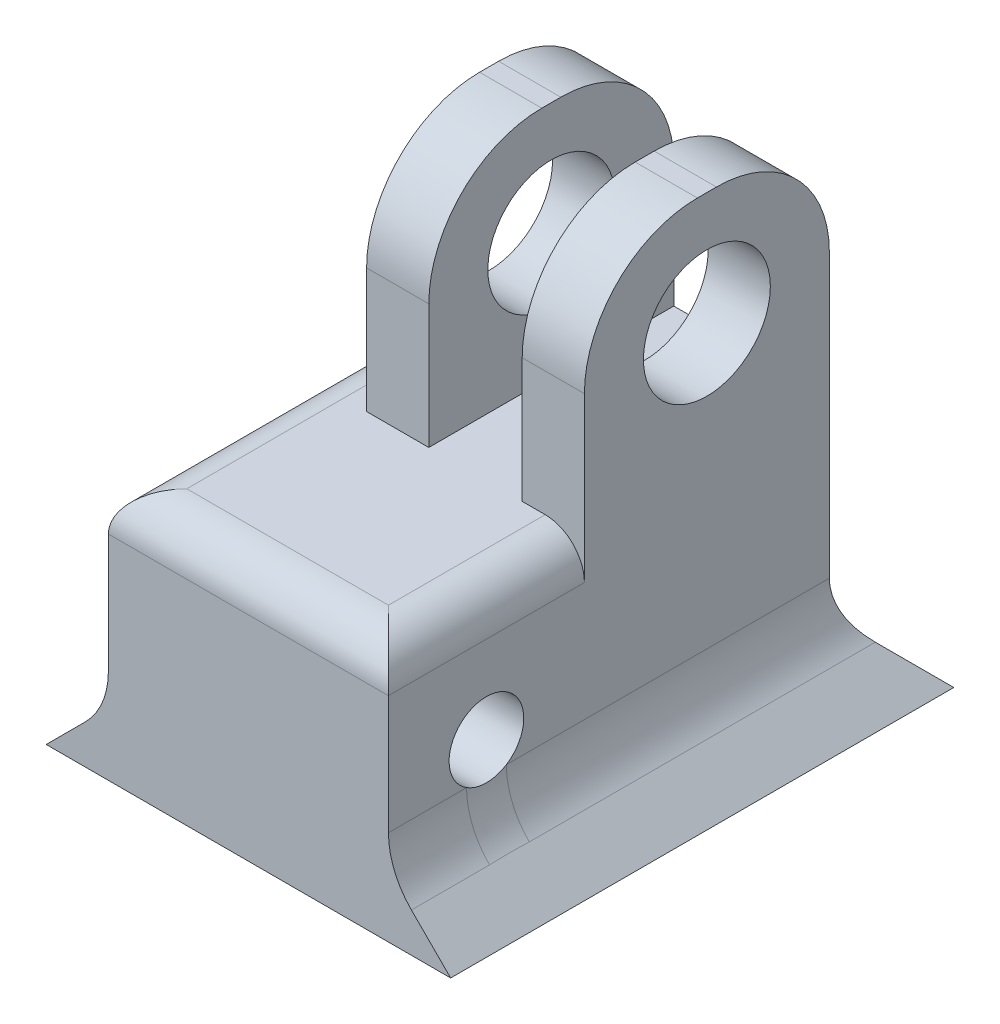
SolidWorks part; units mm, degrees
ref_plane "Front Plane" through (0, 0, 0) normal (0, 0, 1) x (1, 0, 0)
ref_plane "Top Plane" through (0, 0, 0) normal (0, 1, 0) x (1, 0, 0)
ref_plane "Right Plane" through (0, 0, 0) normal (1, 0, 0) x (0, 0, -1)
sketch "Sketch1" plane through (0, 0, 0) normal (0, 0, 1) x (1, 0, 0)
  line L1 (-14.29, -25) -> (14.29, -25)
  line L2 (-14.29, -25) -> (-14.29, 25)
  line L3 (-14.29, 25) -> (14.29, 25)
  line L4 (14.29, -25) -> (14.29, 25)
  line L5 (-14.29, -25) -> (14.29, 25) construction
  line L6 (-14.29, 25) -> (14.29, -25) construction
  point P0 (0, 0)
  dimension "D1" = 50
  dimension "D2" = 28.58
extrude "Boss-Extrude1" add sketch "Sketch1" along normal mid plane 25
sketch "Sketch2" plane through (0, 0, 12.5) normal (0, 0, 1) x (-1, 0, 0)
  line L1 (-7.94, -0.775) -> (1.59, -0.775)
  line L2 (-7.94, -0.775) -> (-7.94, -25)
  line L3 (-7.94, -25) -> (1.59, -25)
  line L4 (1.59, -0.775) -> (1.59, -25)
  line L5 (7.94, -0.775) -> (14.29, -0.775)
  line L6 (7.94, -0.775) -> (7.94, -25)
  line L7 (7.94, -25) -> (14.29, -25)
  line L8 (14.29, -0.775) -> (14.29, -25)
  line L10 (-14.29, -25) -> (14.29, -25) construction
  line L11 (14.29, -25) -> (14.29, 25) construction
  line L12 (-14.29, 25) -> (-14.29, -25) construction
  dimension "D1" = 6.35
  dimension "D2" = 6.35
  dimension "D3" = 24.225
  dimension "D4" = 6.35
extrude "Cut-Extrude1" cut sketch "Sketch2" against normal through all
fillet "Fillet1" radius 11.53 4 edges at (-4.765, 25, -12.5) (-4.765, 25, 12.5) (11.115, 25, 12.5) (11.115, 25, -12.5)
sketch "Sketch3" plane through (14.29, 0, 0) normal (1, 0, 0) x (0, 0, -1)
  line L0 (-11.4063, 13.47) -> (20.1617, 13.47) construction
  line L1 (0, 37.5) -> (0, -49962.5) construction
  line L2 (-0.97, 25) -> (0.97, 25) construction
  circle A0 centre (0, 13.47) radius 6.477
  point P9 (0, 25)
  dimension "D1" = 12.954
extrude "Cut-Extrude2" cut sketch "Sketch3" against normal through all
sketch "Sketch4" plane through (14.29, 0, 0) normal (1, 0, 0) x (0, 0, -1)
  line L0 (-15.659, -25) -> (49984.341, -25) construction
  line L2 (-12.5, -25) -> (12.5, -25) construction
  line L3 (18.85, -25) -> (12.5, -18.65)
  line L4 (12.5, -25) -> (12.5, 13.47) construction
  line L5 (12.5, -18.65) -> (12.5, -25)
  line L6 (12.5, -25) -> (18.85, -25)
  dimension "D1" = 6.35
  dimension "D2" = 45
extrude "Boss-Extrude2" add sketch "Sketch4" against normal up to surface (28.58 mm away) up to face at (-14.29, -12.1125, 0)
sketch "Sketch5" plane through (0, 0, 12.5) normal (0, 0, 1) x (1, 0, 0)
  line L0 (-1.59, 0.775) -> (7.94, 0.775) construction
  line L1 (-14.29, -25) -> (14.29, -25)
  line L2 (-14.29, -25) -> (-14.29, 0.775)
  line L3 (-14.29, 0.775) -> (14.29, 0.775)
  line L4 (14.29, -25) -> (14.29, 0.775)
  line L5 (14.29, -25) -> (14.29, 13.47) construction
extrude "Boss-Extrude3" add sketch "Sketch5" along normal blind 20
sketch "Sketch6" plane through (14.29, 0, 0) normal (1, 0, 0) x (0, 0, -1)
  line L0 (-22.5, 0.775) -> (-22.5, -27.4392) construction
  line L2 (-29.7474, -12.1125) -> (-35.2025, -12.1125) construction
  line L4 (-32.5, 0.775) -> (-12.5, 0.775) construction
  circle A0 centre (-22.5, -12.1125) radius 3.81
  point P10 (-22.5, 0.775)
  dimension "D1" = 7.62
extrude "Cut-Extrude3" cut sketch "Sketch6" against normal through all both and the other way through all
sketch "Sketch7" plane through (0, 0, -12.5) normal (0, 0, -1) x (-1, 0, 0)
  line L0 (-14.29, -25) -> (-20.64, -25)
  line L1 (-20.64, -25) -> (-14.29, -18.65)
  line L2 (-14.29, -18.65) -> (-14.29, 13.47) construction
  line L3 (14.29, -25) -> (-14.29, -25) construction
  line L4 (-14.29, -25) -> (-14.29, -18.65) construction
  line L5 (-14.29, -18.65) -> (-14.29, -25)
  dimension "D1" = 45
  dimension "D2" = 6.35
extrude "Boss-Extrude4" add sketch "Sketch7" against normal up to surface and the other way up to surface up to face at (0, -12.1125, 32.5) other way up to face at (0, -21.825, -15.675)
mirror "Mirror2" about plane through (0, 0, 0) normal (1, 0, 0) of "Boss-Extrude4"
hole_wizard "Ø5.0mm Dowel Hole1" positions "Sketch9" profile "Sketch11" hole size "Ø5.0" standard "ANSI Metric"
sketch "Sketch9" plane through (0, -25, 0) normal (0, -1, 0) x (-1, 0, 0)
  point P0 (-7.5, 0.5343)
  point P3 (7.5, 0.5343)
  point P6 (7.5, -14.4657)
  point P9 (-7.5, -14.4657)
sketch "Sketch11" plane through (7.5, -25, -0.5343) normal (1, 0, 0) x (0, 0, -1)
  line L0 (0, 0) -> (0, 11.5022)
  line L1 (0, 11.5022) -> (2.5, 10)
  line L2 (2.5, 10) -> (2.5, 0)
  line L5 (2.5, 0) -> (0, 0)
  line L10 (0, 11.5022) -> (-2.5, 10) construction
  line L11 (0, -6.35) -> (0, 107.95) construction
  dimension "Hole Dia." = 5
  dimension "Hole Depth" = 10
  dimension "Drill Angle" = 118
fillet "Fillet2" radius 8 3 edges at (-14.29, -18.65, 10) (14.29, -18.65, 10) (0, -18.65, -12.5)
fillet "Fillet4" radius 4 3 edges at (14.29, 0.775, 22.5) (0, 0.775, 32.5) (-14.29, 0.775, 10)
